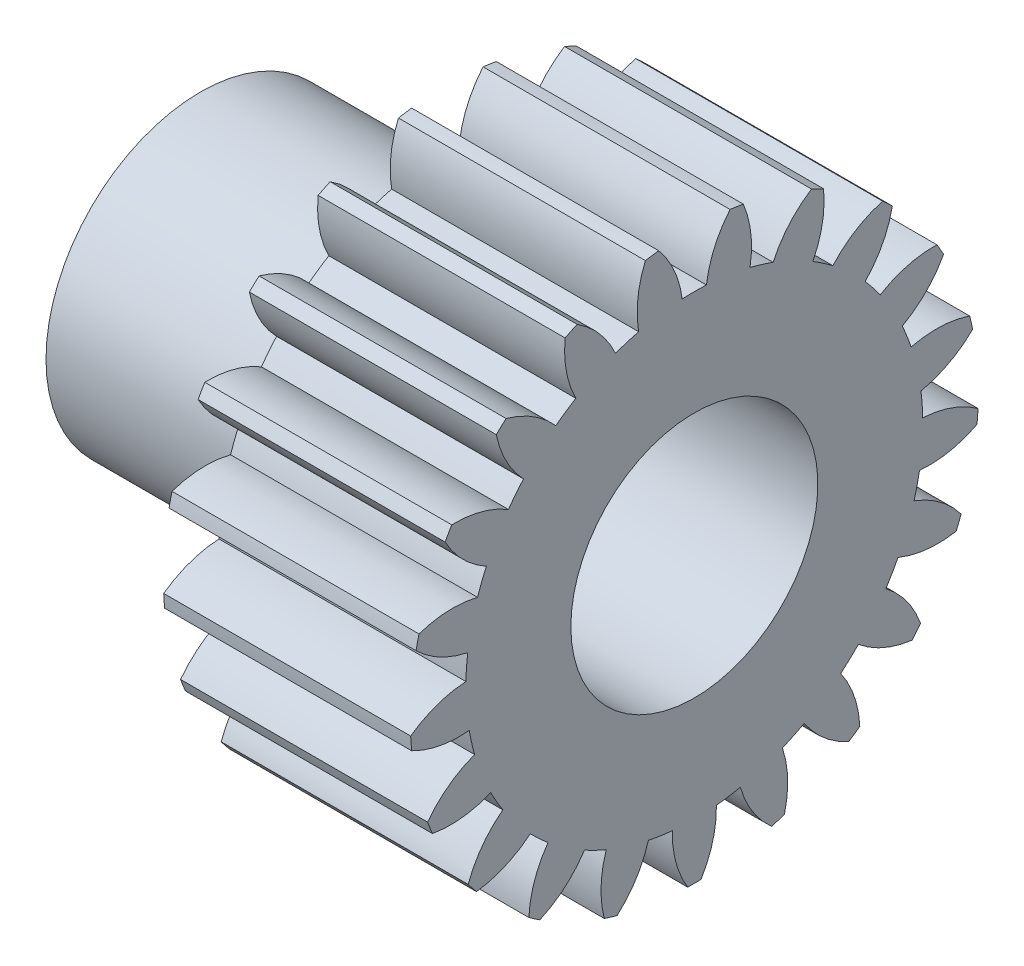
SolidWorks part; units mm, degrees
ref_plane "Plane1" through (0, 0, 0) normal (0, 0, 1) x (1, 0, 0)
ref_plane "Plane2" through (0, 0, 0) normal (0, 1, 0) x (1, 0, 0)
ref_plane "Plane3" through (0, 0, 0) normal (1, 0, 0) x (0, 0, -1)
sketch "HoldingSke" plane through (0, 0, 0) normal (0, 1, 0) x (1, 0, 0)
  line L0 (0, 0) -> (0.1556, -0.0597)
  line L1 (-15, 0) -> (100, 0) construction
  line L2 (0, 0) -> (-2.1039, 2.3779)
  line L3 (0, 0) -> (-11.863, 4.5341)
  line L4 (0, 0) -> (8.0624, 3.0949)
  line L5 (0, 0) -> (-112.4343, -41.9347)
  line L6 (0, 0) -> (-49.7378, -33.5582)
  line L7 (-2.1039, 2.3779) -> (23.726, 119.565)
  line L8 (-76.2, 54.61) -> (-71.8, 54.61)
  line L9 (-71.009, 38.7566) -> (-53.1078, 45.2721)
  line L10 (-76.2, 71.12) -> (104.1128, 71.12)
  line L11 (0, 0) -> (-60, 0)
  line L12 (-76.2, 101.6) -> (-75.993, 101.6)
  line L13 (24.9733, 27.94) -> (52.9518, 28.4284)
  line L14 (24.9733, 27.94) -> (24.9743, 27.94)
  line L15 (24.9733, 27.94) -> (100.4006, 29.5858)
  line L16 (-63.627, -6) -> (-12.827, -6)
  circle A0 centre (0, 0) radius 30
  circle A1 centre (0, 0) radius 37.5
  circle A2 centre (0, 0) radius 37.5
  circle A3 centre (0, 0) radius 30
  dimension "MHD" = 75
  dimension "Hub_dia" = 75
  dimension "Bore" = 60
  dimension "MBD" = 60
  dimension "Num_teeth" = 21
  dimension "Pitch" = 0.1667
  dimension "Overall_len" = 120
  dimension "Show_teeth" = 21
  dimension "Thickness" = 60
  dimension "OAL" = 120.0001
  dimension "T_dim" = 4.4
  dimension "Ap" = 20
  dimension "H" = 19.05
  dimension "Pitch_radius" = 180.3128
  dimension "Width" = 60
  dimension "Backlash" = 0.207
  dimension "Addendum_fac" = 1
  dimension "Dedendum_fac" = 1.25
  dimension "Clearance_fac" = 0.25
  dimension "Dedendum_add" = 0.001
  dimension "Module" = 6
sketch "BasProSke" plane through (0, 0, 0) normal (0, 1, 0) x (1, 0, 0)
  line L0 (-10, 0) -> (60, 0) construction
  line L1 (0, 0) -> (0, 69)
  line L2 (0, 0) -> (60, 0)
  line L3 (60, 0) -> (60, 69)
  line L4 (60, 69) -> (0, 69)
  dimension "Thickness" = 60
  dimension "Diameter" = 138
revolve "Base-Revolve" add sketch "BasProSke" angle 360 about L0
sketch "TooCutSke" plane through (0, 0, 0) normal (1, 0, 0) x (0, 0, -1)
  line L1 (0, 0) -> (0, 107) construction
  line L2 (0, 0) -> (-5.0701, 62.7957) construction
  line L3 (0, 0) -> (-18.7346, 124.2959) construction
  line L4 (-5.0701, 62.7957) -> (-9.3673, 62.148) construction
  arc A0 (2.9399, 55.4211) -> (-2.9399, 55.4211) centre (0, 0) ccw
  arc A1 (8.6963, 68.4754) -> (-8.6963, 68.4754) centre (0, 0) ccw
  circle A2 centre (0, 0) radius 63 construction
  circle A3 centre (0, 0) radius 59.2006 construction
  arc A4 (-2.9399, 55.4211) -> (-8.6963, 68.4754) centre (-27.9327, 52.1965) ccw
  arc A5 (8.6963, 68.4754) -> (2.9399, 55.4211) centre (27.9327, 52.1965) ccw
  dimension "Root_dia" = 110.998
  dimension "Overcut_dia" = 138.0508
  dimension "Pitch_dia" = 126
  dimension "Base_dia" = 118.4013
  dimension "Flank_rad" = 25.2
  dimension "Half_ang" = 8.571
  dimension "Half_CT" = 4.3457
extrude "ToothCut" cut sketch "TooCutSke" along normal through all
fillet "Breaks" [suppressed] radius 0.12
fillet "RootFillets" [suppressed] radius 1.501
pattern_circular "TeethCuts" count 21 every 17.143 about axis through (-10, 0, 0) along (1, 0, 0) of "ToothCut", "RootFillets", "Breaks"
sketch "HubNeaOneSke" plane through (0, 0, 0) normal (-1, 0, 0) x (0, 0, 1)
  circle A0 centre (0, 0) radius 37.5
  dimension "Diameter" = 75
extrude "HubNearOne" add sketch "HubNeaOneSke" along normal blind 60.0001
sketch "HubNeaBotSke" plane through (0, 0, 0) normal (-1, 0, 0) x (0, 0, 1)
  circle A0 centre (0, 0) radius 37.5
  dimension "Diameter" = 75
extrude "HubNearBoth" [suppressed] add sketch "HubNeaBotSke" along normal blind 30
ref_plane "FarPln" through (60, 0, 0) normal (1, 0, 0) x (0, 0, -1)
sketch "HubFarSke" plane through (60, 0, 0) normal (1, 0, 0) x (0, 0, -1)
  circle A0 centre (0, 0) radius 37.5
  dimension "Diameter" = 75
extrude "HubFar" [suppressed] add sketch "HubFarSke" along normal blind 30
sketch "BorSke" plane through (0, 0, 0) normal (1, 0, 0) x (0, 0, -1)
  circle A0 centre (0, 0) radius 30
  dimension "Diameter" = 60
extrude "Bore" cut sketch "BorSke" along normal mid plane 240.0001
sketch "KeySke" plane through (0, 0, 0) normal (1, 0, 0) x (0, 0, -1)
  line L0 (-9, 0) -> (-9, 34.4)
  line L1 (-9, 34.4) -> (9, 34.4)
  line L2 (9, 34.4) -> (9, 0)
  line L3 (0, 0) -> (0, 34) construction
  line L4 (-9, 0) -> (9, 0)
  dimension "Offset" = 34.4
  dimension "Width" = 18
extrude "Keyway" [suppressed] cut sketch "KeySke" along normal mid plane 240.0001
pattern_circular "Keyway2" [suppressed] count 2 every 90 about axis through (-10, 0, 0) along (1, 0, 0)
equation "' \"Module@HoldingSke\" = 6.35"
equation "' \"Num_teeth@HoldingSke\" = 12"
equation "' \"Ap@HoldingSke\" =  20"
equation "' \"Ap@HoldingSke\" = 20"
equation "' \"Width@HoldingSke\" = 0.5 * 25.4"
equation "' \"Hub_dia@HoldingSke\"= 1 * 25.4"
equation "' \"Hub_dia@HoldingSke\" = 1 * 25.4"
equation "' \"Overall_len@HoldingSke\" = 1.0 * 25.4"
equation "' \"Bore@HoldingSke\" = 0.75 * 25.4"
equation "' \"T_dim@HoldingSke\" = 0.1 * 25.4"
equation "' \"Width@KeySke\" = 0.25 * 25.4"
equation "' \"Show_teeth@HoldingSke\" = 13"
equation "' \"Backlash@HoldingSke\" = 0.009 * 25.4"
equation "' \"Addendum_fac@HoldingSke\" = 1.0"
equation "' \"Dedendum_fac@HoldingSke\" = 1.25"
equation "' \"Dedendum_add@HoldingSke\" = 0.00005 * 25.4"
equation "' \"Clearance_fac@HoldingSke\" = 0.25"
equation "\"Pitch@HoldingSke\" = 1 / \"Module@HoldingSke\""
equation "\"Overcut_dia@TooCutSke\" = (\"Num_teeth@HoldingSke\" + 2 * \"Addendum_fac@HoldingSke\") / \"Pitch@HoldingSke\" + 0.002 * 25.4"
equation "\"Pitch_dia@TooCutSke\" = \"Num_teeth@HoldingSke\" / \"Pitch@HoldingSke\""
equation "\"Base_dia@TooCutSke\" = \"Num_teeth@HoldingSke\" / \"Pitch@HoldingSke\" * cos((\"Ap@HoldingSke\"  * 3.14159265 / 180))"
equation "\"Root_dia@TooCutSke\" = (\"Num_teeth@HoldingSke\" + 2) / \"Pitch@HoldingSke\" - 2 * (\"Addendum_fac@HoldingSke\" + \"Dedendum_fac@HoldingSke\") / \"Pitch@HoldingSke\" - \"Dedendum_add@HoldingSke\" * 2"
equation "\"Half_ang@TooCutSke\" = 180 / \"Num_teeth@HoldingSke\""
equation "\"Half_CT@TooCutSke\" = \"Num_teeth@HoldingSke\" / \"Pitch@HoldingSke\" * sin((3.14159265 / 2 / \"Num_teeth@HoldingSke\")) / 2 - 7 * \"Backlash@HoldingSke\" / 4"
equation "\"Flank_rad@TooCutSke\" = \"Num_teeth@HoldingSke\" / \"Pitch@HoldingSke\" / 5"
equation "\"Radius@RootFillets\" = \"Clearance_fac@HoldingSke\" / \"Pitch@HoldingSke\" + \"Dedendum_add@HoldingSke\""
equation "\"Break_rad@Breaks\" = 0.02 / \"Pitch@HoldingSke\""
equation "\"Thickness@HoldingSke\" = \"Width@HoldingSke\""
equation "\"OAL@HoldingSke\" = \"Thickness@HoldingSke\""
equation "\"MHD@HoldingSke\" = (\"Num_teeth@HoldingSke\" + 2) / \"Pitch@HoldingSke\" - 2 * (\"Addendum_fac@HoldingSke\" + \"Dedendum_fac@HoldingSke\")  / \"Pitch@HoldingSke\" - \"Dedendum_add@HoldingSke\" * 2"
equation "\"MBD@HoldingSke\" = (\"Num_teeth@HoldingSke\" + 2) / \"Pitch@HoldingSke\" - 2 * (\"Addendum_fac@HoldingSke\" + \"Dedendum_fac@HoldingSke\")  / \"Pitch@HoldingSke\" - \"Dedendum_add@HoldingSke\" * 2 - 0.002 * 25.4"
equation "\"MHD@HoldingSke\" = ((sgn( \"MHD@HoldingSke\" - \"Hub_dia@HoldingSke\" )-1)*( \"MHD@HoldingSke\" - \"Hub_dia@HoldingSke\" ))/-2+ \"Hub_dia@HoldingSke\""
equation "\"MBD@HoldingSke\" = ((sgn( \"MBD@HoldingSke\" - \"Bore@HoldingSke\" )-1)*( \"MBD@HoldingSke\" - \"Bore@HoldingSke\" ))/-2+ \"Bore@HoldingSke\""
equation "\"OAL@HoldingSke\" = ((sgn( \"OAL@HoldingSke\" - \"Overall_len@HoldingSke\" )+1)*( \"OAL@HoldingSke\" - \"Overall_len@HoldingSke\" ))/2 + \"Overall_len@HoldingSke\" + 0.000002 * 25.4"
equation "\"Num_teeth@TeethCuts\" = int( \"Show_teeth@HoldingSke\" ) + 1"
equation "\"Num_teeth@TeethCuts\" = ((sgn( \"Num_teeth@TeethCuts\" - \"Num_teeth@HoldingSke\" )-1)*( \"Num_teeth@TeethCuts\" - \"Num_teeth@HoldingSke\" ))/-2+ \"Num_teeth@HoldingSke\""
equation "\"Num_teeth@TeethCuts\" = ((sgn( \"Num_teeth@TeethCuts\" - 2.0)+1)*( \"Num_teeth@TeethCuts\" - 2.0))/2 +2.0"
equation "\"Angle@TeethCuts\" = 360.0 / \"Num_teeth@HoldingSke\""
equation "\"Diameter@BasProSke\" = (\"Num_teeth@HoldingSke\" + 2 * \"Addendum_fac@HoldingSke\") / \"Pitch@HoldingSke\""
equation "\"Thickness@BasProSke\"  = \"Thickness@HoldingSke\""
equation "' \"Fillet_rad@BasProSke\" =  \"Thickness@HoldingSke\" * 0.05"
equation "' \"Fillet_rad@BasProSke\" = \"Thickness@HoldingSke\" * 0.05"
equation "\"MHD@HoldingSke\" = ((sgn( \"MHD@HoldingSke\" - \"Root_dia@TooCutSke\" )-1)*( \"MHD@HoldingSke\" - \"Root_dia@TooCutSke\" ))/-2+ \"Root_dia@TooCutSke\""
equation "\"Diameter@HubNeaOneSke\" = \"MHD@HoldingSke\""
equation "\"Length@HubNearOne\" = \"OAL@HoldingSke\" - \"Thickness@BasProSke\""
equation "\"Diameter@HubNeaBotSke\" = \"MHD@HoldingSke\""
equation "\"Length@HubNearBoth\" = ( \"OAL@HoldingSke\" - \"Thickness@BasProSke\" ) / 2.0"
equation "\"Thickness@FarPln\" = \"Thickness@BasProSke\""
equation "\"Diameter@HubFarSke\" = \"MHD@HoldingSke\""
equation "\"Length@HubFar\" = ( \"OAL@HoldingSke\" - \"Thickness@BasProSke\" ) / 2.0"
equation "\"Diameter@BorSke\" = \"MBD@HoldingSke\""
equation "\"D1@Bore\" = \"OAL@HoldingSke\" * 2.0"
equation "\"D1@Keyway\" = \"OAL@HoldingSke\" * 2.0"
equation "\"Offset@KeySke\" = \"T_dim@HoldingSke\" + \"MBD@HoldingSke\" / 2.0"
